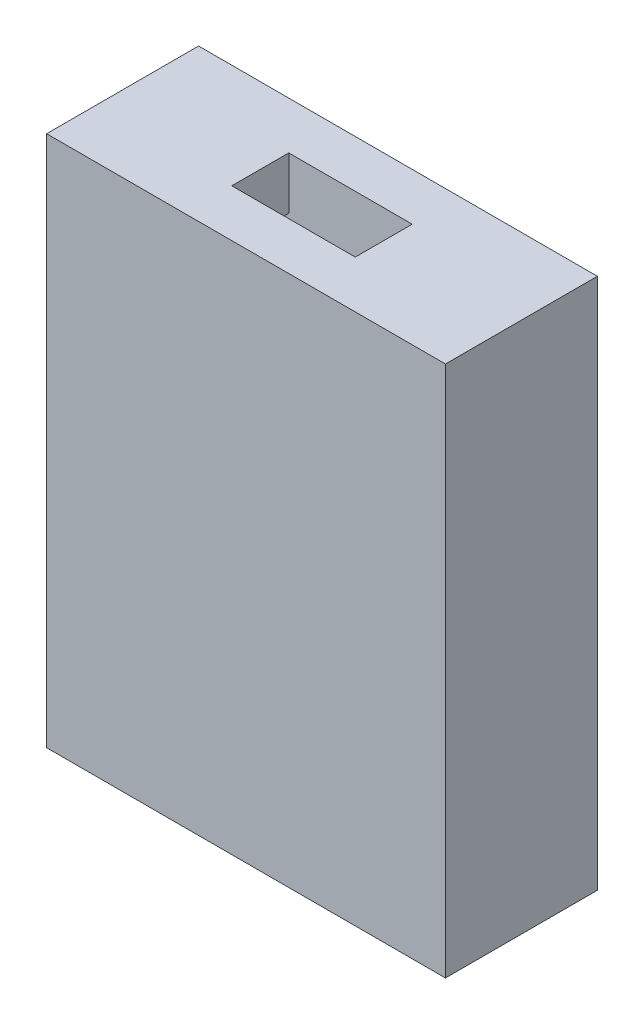
SolidWorks part; units mm, degrees
ref_plane "Plan de face" through (0, 0, 0) normal (0, 0, 1) x (1, 0, 0)
ref_plane "Plan de dessus" through (0, 0, 0) normal (0, 1, 0) x (1, 0, 0)
ref_plane "Plan de droite" through (0, 0, 0) normal (1, 0, 0) x (0, 0, -1)
sketch "Esquisse1" plane through (0, 0, 0) normal (0, 1, 0) x (1, 0, 0)
  line L1 (-21, 8) -> (21, 8)
  line L2 (-21, 8) -> (-21, -8)
  line L3 (-21, -8) -> (21, -8)
  line L4 (21, 8) -> (21, -8)
  line L5 (-21, 8) -> (21, -8) construction
  line L6 (-21, -8) -> (21, 8) construction
  point P0 (0, 0)
  dimension "D1" = 42
  dimension "D2" = 16
extrude "Boss.-Extru.1" add sketch "Esquisse1" along normal blind 56
sketch "Esquisse2" plane through (0, 56, 0) normal (0, 1, 0) x (1, 0, 0)
  line L1 (-6.5, -3) -> (6.5, -3)
  line L2 (-6.5, -3) -> (-6.5, 3)
  line L3 (-6.5, 3) -> (6.5, 3)
  line L4 (6.5, -3) -> (6.5, 3)
  line L5 (-6.5, -3) -> (6.5, 3) construction
  line L6 (-6.5, 3) -> (6.5, -3) construction
  point P0 (0, 0)
  dimension "D1" = 13
  dimension "D2" = 6
extrude "Enlèv. mat.-Extru.1" cut sketch "Esquisse2" against normal blind 11
sketch "Esquisse3" plane through (-6.5, 0, 0) normal (1, 0, 0) x (0, 0, -1)
  line L0 (3, 45) -> (3, 56) construction
  line L1 (-3, 45) -> (3, 45)
  line L2 (-3, 45) -> (-3, 50.5)
  line L3 (-3, 50.5) -> (3, 50.5)
  line L4 (3, 45) -> (3, 50.5)
extrude "Enlèv. mat.-Extru.2" cut sketch "Esquisse3" against normal through all
